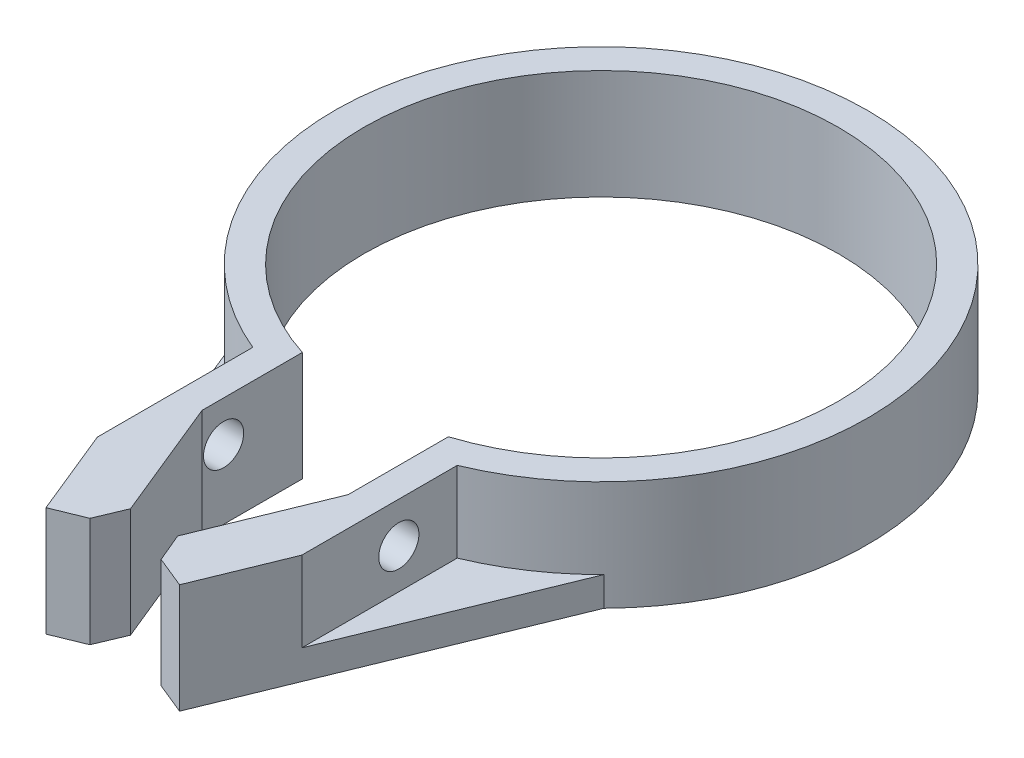
SolidWorks part; units mm, degrees
ref_plane "Front Plane" through (0, 0, 0) normal (0, 0, 1) x (1, 0, 0)
ref_plane "Top Plane" through (0, 0, 0) normal (0, 1, 0) x (1, 0, 0)
ref_plane "Right Plane" through (0, 0, 0) normal (1, 0, 0) x (0, 0, -1)
sketch "Sketch1" plane through (0, 0, 0) normal (0, 1, 0) x (1, 0, 0)
  line L2 (-14, -33.7083) -> (-14, -55)
  line L3 (-14, -55) -> (-10, -55)
  line L4 (-10, -30.9233) -> (-10, -55)
  line L6 (10, -30.9233) -> (10, -55)
  line L7 (10, -55) -> (14, -55)
  line L8 (14, -33.7083) -> (14, -55)
  arc A0 (10, -30.9233) -> (-10, -30.9233) centre (0, 0) ccw
  arc A1 (14, -33.7083) -> (-14, -33.7083) centre (0, 0) ccw
  point P14 (4.9934, -32.1141)
  dimension "D1" = 65
  dimension "D2" = 4
  dimension "D5" = 10
  dimension "D6" = 10
  dimension "D7" = 55
  dimension "D8" = 55
extrude "Boss-Extrude1" add sketch "Sketch1" along normal blind 15
sketch "Sketch2" plane through (0, 0, 0) normal (0, -1, 0) x (1, 0, 0)
  line L0 (-26, 22.8569) -> (-14, 33.7083)
  line L1 (-14, 55) -> (-26, 55)
  line L2 (-14, 55) -> (-14, 33.7083)
  line L4 (-26, 55) -> (-26, 22.8569)
  line L5 (14, 55) -> (26, 55)
  line L6 (14, 55) -> (14, 33.7083)
  line L8 (26, 55) -> (26, 22.8569)
  line L9 (26, 22.8569) -> (14, 33.7083)
  dimension "D1" = 12
  dimension "D2" = 12
extrude "Boss-Extrude2" add sketch "Sketch2" against normal blind 4
sketch "Sketch4" plane through (0, 4, 0) normal (0, 1, 0) x (1, 0, 0)
  line L0 (-26, -25.6174) -> (-14, -55)
  line L1 (-14, -55) -> (-32.3232, -64.2596)
  line L2 (-32.3232, -64.2596) -> (-26, -25.6174)
  line L3 (14, -55) -> (26, -25.6174)
  line L4 (26, -25.6174) -> (31.2251, -59.6298)
  line L5 (31.2251, -59.6298) -> (14, -55)
extrude "Cut-Extrude1" cut sketch "Sketch4" against normal blind 4
sketch "Sketch5" plane through (0, 0, 0) normal (0, -1, 0) x (1, 0, 0)
  line L0 (-14, 55) -> (-9.1461, 66.8851)
  line L1 (-9.1461, 66.8851) -> (-2.0967, 64.0061)
  line L2 (-2.0967, 64.0061) -> (-10, 44.6544)
  line L3 (-10, 55) -> (-10, 30.9233) construction
  line L4 (-10, 44.6544) -> (-14, 55)
  line L5 (14, 55) -> (9.1461, 66.8851)
  line L6 (9.1461, 66.8851) -> (2.0967, 64.0061)
  line L7 (14, 55) -> (10, 55)
  line L8 (2.0967, 64.0061) -> (10, 44.6544)
  line L9 (10, 30.9233) -> (10, 55) construction
  line L10 (10, 44.6544) -> (14, 55)
  line M4 (14, 55) -> (10, 55)
  line M5 (10, 55) -> (10, 30.9233)
  line M7 (-10, 30.9233) -> (-10, 55)
  line M8 (-10, 55) -> (-14, 55)
extrude "Boss-Extrude3" add sketch "Sketch5" against normal blind 15 contours L2 L1 L0 M8 M7 | L6 L8 L5 M5 M4
chamfer "Chamfer1" distance 3 angle 45 2 edges at (2.0967, 7.5, 64.0061) (-2.0967, 7.5, 64.0061)
sketch "Sketch6" plane through (14, 0, 0) normal (1, 0, 0) x (0, 0, -1)
  line L0 (-33.7083, 15) -> (-33.7083, 4) construction
  circle A0 centre (-41.7083, 9.4665) radius 2.75
  dimension "D1" = 5.5
  dimension "D2" = 8
extrude "Cut-Extrude2" cut sketch "Sketch6" against normal blind 50
